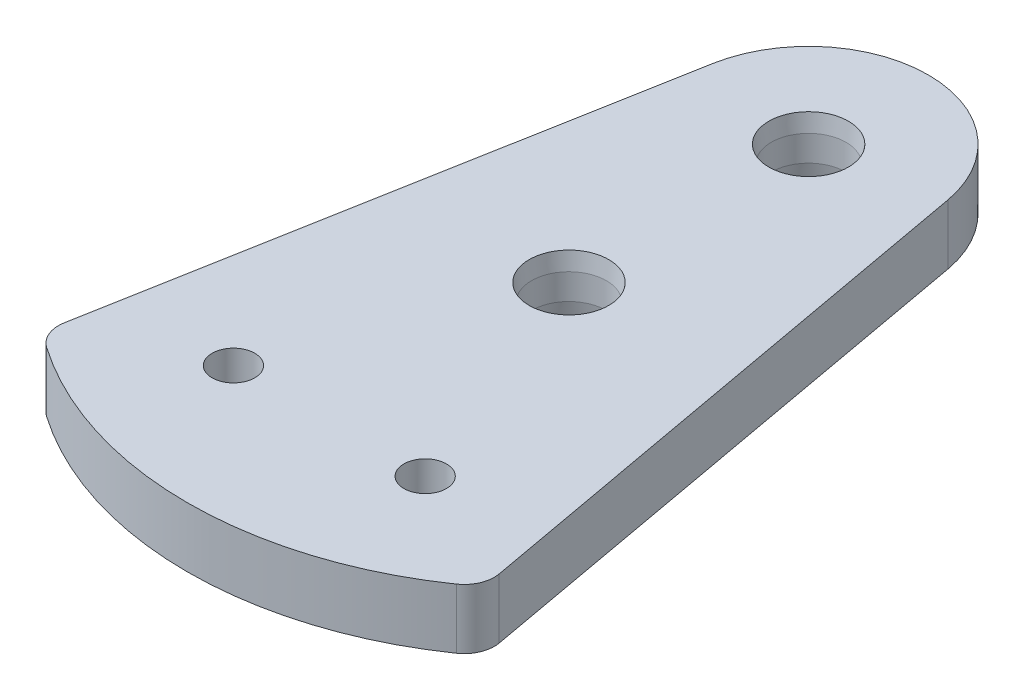
SolidWorks part; units mm, degrees
material "Stainless Steel (ferritic)"
ref_plane "Front Plane" through (0, 0, 0) normal (0, 0, 1) x (1, 0, 0)
ref_plane "Top Plane" through (0, 0, 0) normal (0, 1, 0) x (1, 0, 0)
ref_plane "Right Plane" through (0, 0, 0) normal (1, 0, 0) x (0, 0, -1)
sketch "Sketch2" plane through (0, 0, 0) normal (0, 1, 0) x (1, 0, 0)
  line L0 (-6.2479, 1.1344) -> (-11.5229, -27.9187)
  line L1 (11.5229, -27.9187) -> (6.2479, 1.1344)
  line L2 (10.8607, -29.5192) -> (11.7069, -28.932) construction
  line L3 (11.5229, -27.9187) -> (11.7069, -28.932) construction
  line L4 (-11.5229, -27.9187) -> (-11.7069, -28.932) construction
  line L5 (-10.8607, -29.5192) -> (-11.7069, -28.932) construction
  line L6 (0, 0) -> (0, -32.9184) construction
  arc A0 (6.2479, 1.1344) -> (-6.2479, 1.1344) centre (0, 0) ccw
  arc A1 (-10.8607, -29.5192) -> (10.8607, -29.5192) centre (0, -13.8684) ccw
  arc A4 (-11.5229, -27.9187) -> (-10.8607, -29.5192) centre (-9.9484, -28.2045) ccw
  arc A5 (11.5229, -27.9187) -> (10.8607, -29.5192) centre (9.9484, -28.2045) cw
  dimension "D1" = 19.05
  dimension "D2" = 6.35
  dimension "D6" = 1.6002
  dimension "D7" = 1.6002
  dimension "D3" = 13.8684
  dimension "D8" = 11.7069
  dimension "D9" = 11.7069
extrude "Boss-Extrude1" add sketch "Sketch2" along normal blind 3.175
sketch "Sketch3" plane through (0, 3.175, 0) normal (0, 1, 0) x (1, 0, 0)
  line L0 (0, 0) -> (0, -25.4) construction
  line L1 (-5.08, -25.4) -> (5.08, -25.4) construction
  circle A0 centre (0, 0) radius 1.9812
  circle A1 centre (0, -12.7) radius 1.9812
  dimension "D3" = 3.9624
  dimension "D4" = 3.9624
  dimension "D1" = 25.4
  dimension "D2" = 10.16
  dimension "D5" = 12.7
hole_wizard "#4-40 Tapped Hole1" positions "Sketch4" profile "Sketch5" tap size "#4-40" standard "ANSI Inch" end condition through all
sketch "Sketch4" plane through (0, 3.175, 0) normal (0, 1, 0) x (1, 0, 0)
  point P0 (-5.08, -25.4)
  point P3 (5.08, -25.4)
sketch "Sketch5" plane through (-5.08, 3.175, 25.4) normal (1, 0, 0) x (0, 0, 1)
  line L0 (0, 0) -> (0, 3.175)
  line L1 (0, 3.175) -> (1.1303, 3.175)
  line L2 (1.1303, 3.175) -> (1.1303, 0)
  line L5 (1.1303, 0) -> (0, 0)
  line L11 (0, -6.35) -> (0, 107.95) construction
  dimension "Thru Tap Drill Dia." = 2.2606
  dimension "Thru Tap Drill Depth" = 3.175
cosmetic thread "Hole Thread1" parameters "D2"=2.8448
cosmetic thread "Hole Thread2" parameters "D2"=2.8448
extrude "Cut-Extrude1" cut sketch "Sketch3" against normal up to next
chamfer "Chamfer1" distance 0.127 angle 82 4 edges at (0, 3.175, 14.6812) (0, 0, 14.6812) (0, 0, 1.9812) (0, 3.175, 1.9812)
sketch "Sketch6" plane through (0, 3.175, 0) normal (0, 1, 0) x (1, 0, 0)
  line L0 (0, 6.35) -> (0, -32.9184) construction
  arc A0 (6.2479, 1.1344) -> (-6.2479, 1.1344) centre (0, 0) ccw construction
  arc A1 (-10.8607, -29.5192) -> (10.8607, -29.5192) centre (0, -13.8684) ccw construction
ref_point "Point1"
ref_point "Point2"
sketch "Sketch7" plane through (0, 0, 0) normal (0, -1, 0) x (1, 0, 0)
  line L0 (0, 12.7) -> (8.7597, 12.7) construction
  line L1 (11.5229, 27.9187) -> (6.2479, -1.1344) construction
  line L2 (0, 12.7) -> (0, -6.35) construction
